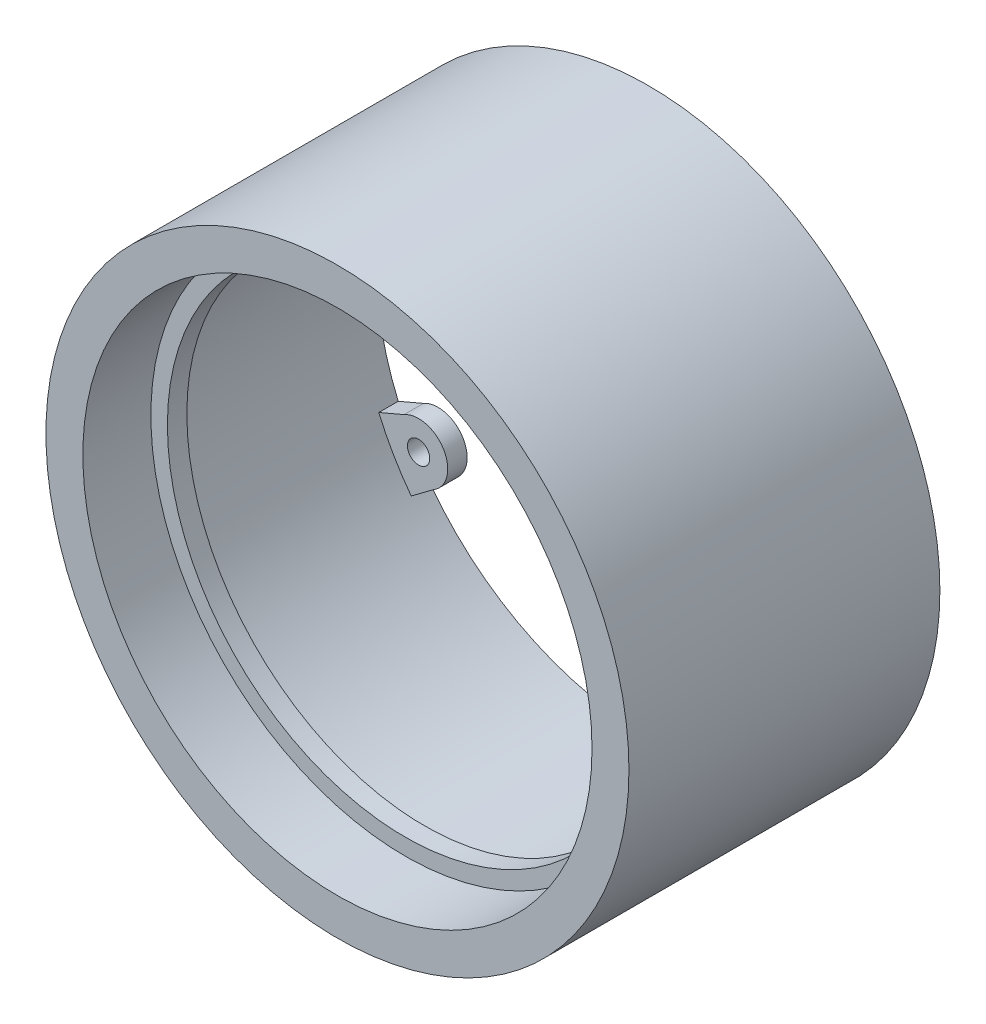
SolidWorks part; units mm, degrees
ref_plane "Alzado" through (0, 0, 0) normal (0, 0, 1) x (1, 0, 0)
ref_plane "Planta" through (0, 0, 0) normal (0, 1, 0) x (1, 0, 0)
ref_plane "Vista lateral" through (0, 0, 0) normal (1, 0, 0) x (0, 0, -1)
sketch "Croquis1" plane through (0, 0, 0) normal (0, 0, 1) x (1, 0, 0)
  circle A0 centre (0, 0) radius 30
  circle A1 centre (0, 0) radius 28
  dimension "D1" = 60
  dimension "D2" = 56
extrude "Saliente-Extruir1" add sketch "Croquis1" along normal blind 23
sketch "Croquis2" plane through (0, 0, 0) normal (0, 0, 1) x (1, 0, 0)
  line L0 (-3, 25) -> (-3.3361, 27.8006)
  line L1 (3, 25) -> (3.3361, 27.8006)
  line L2 (20.1506, 15.0981) -> (22.408, 16.7894)
  line L3 (23.1506, 9.9019) -> (25.744, 11.0112)
  line L4 (23.1506, -9.9019) -> (25.744, -11.0112)
  line L5 (20.1506, -15.0981) -> (22.408, -16.7894)
  line L8 (-20.1506, -15.0981) -> (-22.408, -16.7894)
  line L9 (-23.1506, -9.9019) -> (-25.744, -11.0112)
  line L10 (-23.1506, 9.9019) -> (-25.744, 11.0112)
  line L11 (-20.1506, 15.0981) -> (-22.408, 16.7894)
  line L12 (3, -25) -> (3.3361, -27.8006) [skipped]
  line L13 (-3, -25) -> (-3.3361, -27.8006) [skipped]
  arc A0 (-3, 25) -> (3, 25) centre (0, 25) ccw
  circle A3 centre (0, 0) radius 28 construction
  arc A4 (-3.3361, 27.8006) -> (3.3361, 27.8006) centre (0, 0) cw
  circle A5 centre (0, 25) radius 1.15
  arc A6 (22.408, 16.7894) -> (25.744, 11.0112) centre (0, 0) cw
  arc A7 (20.1506, 15.0981) -> (23.1506, 9.9019) centre (21.6506, 12.5) ccw
  circle A8 centre (21.6506, 12.5) radius 1.15
  arc A9 (25.744, -11.0112) -> (22.408, -16.7894) centre (0, 0) cw
  arc A10 (23.1506, -9.9019) -> (20.1506, -15.0981) centre (21.6506, -12.5) ccw
  circle A11 centre (21.6506, -12.5) radius 1.15
  arc A15 (-22.408, -16.7894) -> (-25.744, -11.0112) centre (0, 0) cw
  arc A16 (-20.1506, -15.0981) -> (-23.1506, -9.9019) centre (-21.6506, -12.5) ccw
  circle A17 centre (-21.6506, -12.5) radius 1.15
  arc A18 (-25.744, 11.0112) -> (-22.408, 16.7894) centre (0, 0) cw
  arc A19 (-23.1506, 9.9019) -> (-20.1506, 15.0981) centre (-21.6506, 12.5) ccw
  circle A20 centre (-21.6506, 12.5) radius 1.15
  arc A21 (3.3361, -27.8006) -> (-3.3361, -27.8006) centre (0, 0) cw [skipped]
  arc A22 (3, -25) -> (-3, -25) centre (0, -25) ccw [skipped]
  circle A23 centre (0, -25) radius 1.15 [skipped]
  point P42 (0, 0)
  dimension "D1" = 6
  dimension "D2" = 2.3
  dimension "D3" = 2.8006
  dimension "D4" = 2.9786
  dimension "D5" = 2.8006
  dimension "D6" = 6
extrude "Saliente-Extruir2" add sketch "Croquis2" along normal blind 2
sketch "Croquis4" plane through (0, 0, 23) normal (0, 0, 1) x (1, 0, 0)
  circle A0 centre (0, 0) radius 30
  circle A1 centre (0, 0) radius 24.5
  dimension "D1" = 60
  dimension "D2" = 49
extrude "Saliente-Extruir3" add sketch "Croquis4" along normal blind 2
sketch "Croquis5" plane through (0, 0, 25) normal (0, 0, 1) x (1, 0, 0)
  circle A0 centre (0, 0) radius 30
  circle A1 centre (0, 0) radius 26.2
  dimension "D1" = 60
  dimension "D2" = 52.4
extrude "Saliente-Extruir4" add sketch "Croquis5" along normal blind 7
